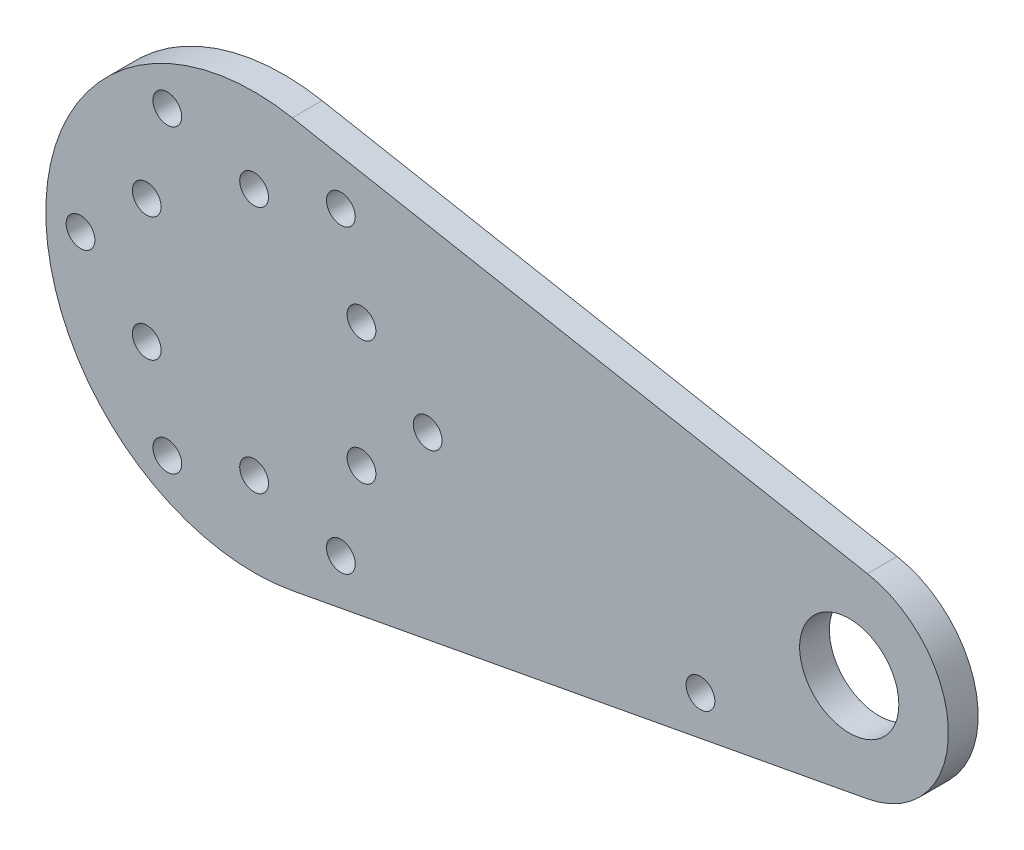
SolidWorks part; units mm, degrees
material "Thornel Mat VMA"
ref_plane "前视基准面" through (0, 0, 0) normal (0, 0, 1) x (1, 0, 0)
ref_plane "上视基准面" through (0, 0, 0) normal (0, 1, 0) x (1, 0, 0)
ref_plane "右视基准面" through (0, 0, 0) normal (1, 0, 0) x (0, 0, -1)
other "Configuration Table"
sketch "草图1" plane through (0, 0, 0) normal (0, 0, 1) x (1, 0, 0)
  line L0 (60, 0) -> (0, 0) construction
  line L1 (61.8333, -9.8305) -> (3.85, -20.6441)
  line L2 (3.85, 20.6441) -> (61.8333, 9.8305)
  arc A0 (3.85, 20.6441) -> (3.85, -20.6441) centre (0, 0) ccw
  circle A1 centre (60, 0) radius 5
  arc A2 (61.8333, -9.8305) -> (61.8333, 9.8305) centre (60, 0) ccw
  circle A3 centre (0, 0) radius 12.5 construction
  circle A4 centre (0, 12.5) radius 1.45
  circle A13 centre (10.8253, 6.25) radius 1.45
  circle A14 centre (10.8253, -6.25) radius 1.45
  circle A15 centre (0, -12.5) radius 1.45
  circle A16 centre (-10.8253, -6.25) radius 1.45
  circle A17 centre (-10.8253, 6.25) radius 1.45
  dimension "D2" = 42
  dimension "D3" = 10
  dimension "D4" = 10
  dimension "D5" = 25
  dimension "D6" = 2.9
  dimension "D1" = 60
extrude "凸台-拉伸1" add sketch "草图1" along normal blind 3
sketch "草图2" plane through (0, 0, 3) normal (0, 0, 1) x (1, 0, 0)
  line L0 (8.75, 15.1554) -> (0, 0) construction
  line L1 (0, 0) -> (70.5723, 0) construction
  circle A0 centre (0, 0) radius 17.5 construction
  circle A1 centre (8.75, 15.1554) radius 1.45
  circle A2 centre (17.5, 0) radius 1.45
  circle A3 centre (8.75, -15.1554) radius 1.45
  circle A4 centre (-8.75, -15.1554) radius 1.45
  circle A5 centre (-17.5, 0) radius 1.45
  circle A6 centre (-8.75, 15.1554) radius 1.45
  circle A7 centre (45, -9) radius 1.45
  dimension "D1" = 35
  dimension "D2" = 2.9
  dimension "D4" = 9
  dimension "D5" = 2.9
  dimension "D3" = 60
  dimension "D6" = 45
extrude "切除-拉伸1" cut sketch "草图2" against normal through all
